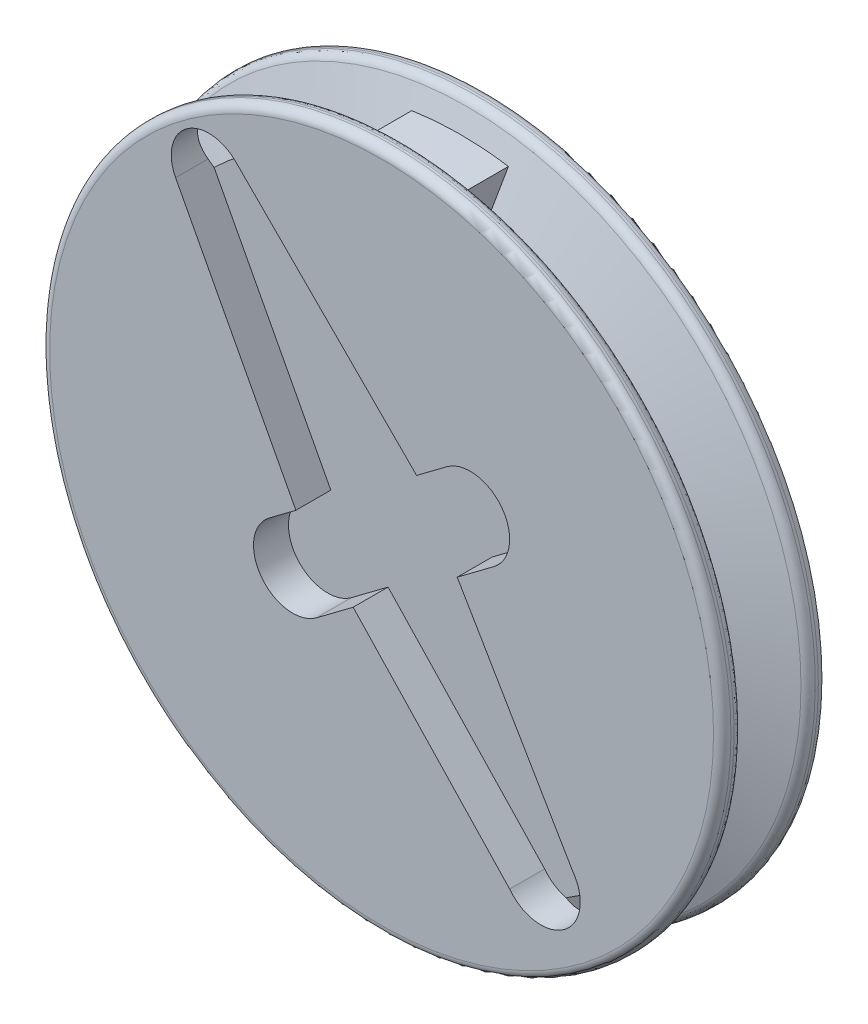
SolidWorks part; units mm, degrees
ref_plane "Front Plane" through (0, 0, 0) normal (0, 0, 1) x (1, 0, 0)
ref_plane "Top Plane" through (0, 0, 0) normal (0, 1, 0) x (1, 0, 0)
ref_plane "Right Plane" through (0, 0, 0) normal (1, 0, 0) x (0, 0, -1)
sketch "Sketch1" plane through (0, 0, 0) normal (0, 0, 1) x (1, 0, 0)
  circle A0 centre (-8.4, 31.2) radius 5.75
  circle A1 centre (-8.4, 31.2) radius 6 construction
  dimension "D1" = 0.25
extrude "Boss-Extrude1" add sketch "Sketch1" against normal blind 1.825
sketch "Sketch2" plane through (0, 0, 0) normal (0, 0, 1) x (1, 0, 0)
  circle A0 centre (-8.4, 31.2) radius 19.5
  dimension "D1" = 39
extrude "Boss-Extrude2" add sketch "Sketch2" along normal blind 6
sketch "Sketch4" plane through (0, 0, 6) normal (0, 0, 1) x (1, 0, 0)
  line L0 (6.6927, 24.5321) -> (-23.4927, 37.8679) construction
  line L1 (-23.1445, 38.8054) -> (-7.5918, 33.0294)
  line L2 (-23.9513, 36.9793) -> (-9.2082, 29.3706)
  line L3 (-9.2082, 29.3706) -> (-7.5918, 33.0294)
  line L4 (-7.5918, 33.0294) -> (7.1513, 25.4207)
  line L5 (-9.2082, 29.3706) -> (5.6948, 24.5976)
  line L6 (-6.9766, 30.5711) -> (-9.8234, 31.8289) construction
  line L7 (-10.5042, 26.6643) -> (-6.2958, 35.7357) construction
  line L8 (-11.4521, 26.9829) -> (-9.8234, 31.8289)
  line L9 (-7.1519, 36.2526) -> (-9.8234, 31.8289)
  line L10 (-11.4514, 26.9848) -> (-6.9766, 30.5711)
  line L11 (-7.2175, 36.1236) -> (-6.9766, 30.5711)
  arc A1 (-23.1445, 38.8054) -> (-23.9513, 36.9793) centre (-23.4927, 37.8679) ccw
  arc A2 (5.6948, 24.5976) -> (7.1513, 25.4207) centre (6.6927, 24.5321) ccw
  circle A3 centre (-8.4, 31.2) radius 19.5 construction
  arc A4 (-7.1804, 35.2694) -> (-7.1519, 36.2526) centre (-6.2958, 35.7357) ccw
  arc A5 (-11.4521, 26.9829) -> (-11.4514, 26.9848) centre (-10.5042, 26.6643) ccw
  arc A6 (-10.0833, 27.5714) -> (-11.4521, 26.9829) centre (-10.5042, 26.6643) ccw construction
  arc A7 (-11.4514, 26.9848) -> (-10.0833, 27.5714) centre (-10.5042, 26.6643) ccw construction
  arc A8 (-6.7167, 34.8286) -> (-7.1804, 35.2694) centre (-6.2958, 35.7357) ccw construction
  arc A9 (-7.1519, 36.2526) -> (-6.7167, 34.8286) centre (-6.2958, 35.7357) ccw construction
  point P10 (-8.4, 31.2)
  point P11 (-8.4, 31.2)
  point P15 (-8.4, 31.2)
  point P17 (-8.4, 31.2)
  dimension "D2" = 2
  dimension "D3" = 4
  dimension "D5" = 2
  dimension "D1" = 33
  dimension "D4" = 10
extrude "Cut-Extrude1" [suppressed] cut sketch "Sketch4" against normal blind 3 contours L8 A5 L10 L5 L2 | L11 L4 L3 L5 L10 | L11 A4 L9 L1 L4 | L1 L9 L8 L2 L3 | L1 A1 L2 L8 L9 | L5 A2 L4 L11 L10
sketch "Sketch5" plane through (0, 0, 6) normal (0, 0, 1) x (1, 0, 0)
  line L16 (-19.3255, 42.0174) -> (-12.2961, 31.0904)
  line L17 (-12.2961, 31.0904) -> (-14.83, 29.19)
  line L18 (-12.13, 25.59) -> (-10.0286, 27.1661)
  line L19 (-10.0286, 27.1661) -> (-1.0712, 17.6784)
  line L20 (2.5287, 20.3783) -> (-4.0714, 31.6339)
  line L21 (-4.0714, 31.6339) -> (-1.97, 33.21)
  line L22 (-4.67, 36.81) -> (-7.2039, 34.9096)
  line L23 (-7.2039, 34.9096) -> (-15.7256, 44.7174)
  line L24 (-19.3255, 42.0174) -> (-12.2961, 31.0904)
  line L25 (-12.2961, 31.0904) -> (-14.83, 29.19)
  line L26 (-12.13, 25.59) -> (-10.0286, 27.1661)
  line L27 (-10.0286, 27.1661) -> (-1.0712, 17.6784)
  line L28 (2.5287, 20.3783) -> (-4.0714, 31.6339)
  line L29 (-4.0714, 31.6339) -> (-1.97, 33.21)
  line L30 (-4.67, 36.81) -> (-7.2039, 34.9096)
  line L31 (-7.2039, 34.9096) -> (-15.7256, 44.7174)
  arc A8 (-15.7256, 44.7174) -> (-19.3255, 42.0174) centre (-17.52, 43.36) ccw
  arc A9 (-14.83, 29.19) -> (-12.13, 25.59) centre (-13.48, 27.39) ccw
  arc A10 (-1.0712, 17.6784) -> (2.5287, 20.3783) centre (0.72, 19.04) ccw
  arc A11 (-1.97, 33.21) -> (-4.67, 36.81) centre (-3.32, 35.01) ccw
  arc A12 (-15.7256, 44.7174) -> (-19.3255, 42.0174) centre (-17.52, 43.36) ccw
  arc A13 (-14.83, 29.19) -> (-12.13, 25.59) centre (-13.48, 27.39) ccw
  arc A14 (-1.0712, 17.6784) -> (2.5287, 20.3783) centre (0.72, 19.04) ccw
  arc A15 (-1.97, 33.21) -> (-4.67, 36.81) centre (-3.32, 35.01) ccw
  dimension "D1" = 0.25
extrude "Cut-Extrude2" cut sketch "Sketch5" against normal blind 2
ref_plane "Plane1" through (-8.4, 0, 0) normal (1, 0, 0) x (0, 0, -1)
sketch "Sketch6" plane through (-8.4, 0, 0) normal (1, 0, 0) x (0, 0, -1)
  line L0 (-5, 50.7) -> (-3, 44.7)
  line L1 (-5, 50.7) -> (-1, 50.7)
  line L4 (-1, 50.7) -> (-3, 44.7)
  line L5 (-3, 11.7) -> (-3, 44.7) construction
  line L6 (-6, 11.7) -> (0, 11.7) construction
  line L8 (0, 50.7) -> (-6, 50.7) construction
  point P10 (-3, 50.7)
  dimension "D1" = 6
  dimension "D2" = 4
sketch "Sketch8" plane through (-8.4, 0, 0) normal (1, 0, 0) x (0, 0, -1)
  line L0 (-6, 31.0904) -> (10.639, 31.0904) construction
revolve "Cut-Revolve2" cut sketch "Sketch6" angle 360 about L0
sketch "Sketch9" plane through (-8.4, 0, 0) normal (1, 0, 0) x (0, 0, -1)
  line L1 (-6, 50.7) -> (-4.5, 51.1899)
  line L2 (-4.5, 51.1899) -> (-1.5, 51.1899)
  line L3 (-1.5, 51.1899) -> (0, 50.7)
  line L4 (0, 11.7) -> (0, 50.7) construction
  line L5 (0, 50.7) -> (-1, 50.7) construction
  line L11 (-6, 50.7) -> (0, 50.7)
  line L13 (-4.5, 50.7) -> (-4.5, 51.1899) construction
  dimension "D2" = 0.7
sketch "Sketch10" plane through (0, 0, 6) normal (0, 0, 1) x (1, 0, 0)
  line L0 (-6.3948, 35.5164) -> (-16.7634, 45.904)
  line L2 (-13.307, 30.3323) -> (-20.1915, 43.3779)
  line L4 (-6.3948, 35.5164) -> (-13.307, 30.3323)
  line L6 (-4.67, 36.81) -> (-7.2039, 34.9096) construction
  line L7 (-12.2961, 31.0904) -> (-14.83, 29.19) construction
  arc A1 (-20.1915, 43.3779) -> (-16.7634, 45.904) centre (-18.2873, 44.3829) cw
extrude "Cut-Extrude3" cut sketch "Sketch10" against normal up to surface (2 mm away) up to face at (-8.3838, 31.1802, 4)
sketch "Sketch11" plane through (-8.4, 0, 0) normal (1, 0, 0) x (0, 0, -1)
  line L0 (-4.5, 47.1821) -> (-1.5, 47.1821)
  line L1 (-1.5, 47.1821) -> (-1.5, 49.1821)
  line L2 (-1.5, 49.1821) -> (-4.5, 49.1821)
  line L3 (-4.5, 49.1821) -> (-4.5, 47.1821)
  dimension "D1" = 2
fillet "Fillet2" radius 0.5 5 edges at (11.1, 31.2, 0) (11.1, 31.2, 6) (4.4342, 45.881, 1.009) (5.2096, 31.0904, 3) (9.6489, 38.5816, 4.9774)
sketch "Sketch13" plane through (0, 0, 0) normal (0, 0, 1) x (1, 0, 0)
  line L0 (-8.4, -9.4042) -> (-8.4, 9.4042) construction
  arc A0 (-11.4, 50.4678) -> (-5.4, 50.4678) centre (-8.4, 31.2) cw
  circle A1 centre (-8.4, 31.2) radius 19.5 construction
  point P6 (-8.4, 50.7)
  dimension "D1" = 6
sweep "Sweep1" add profiles "Sketch11" path "Sketch13"
